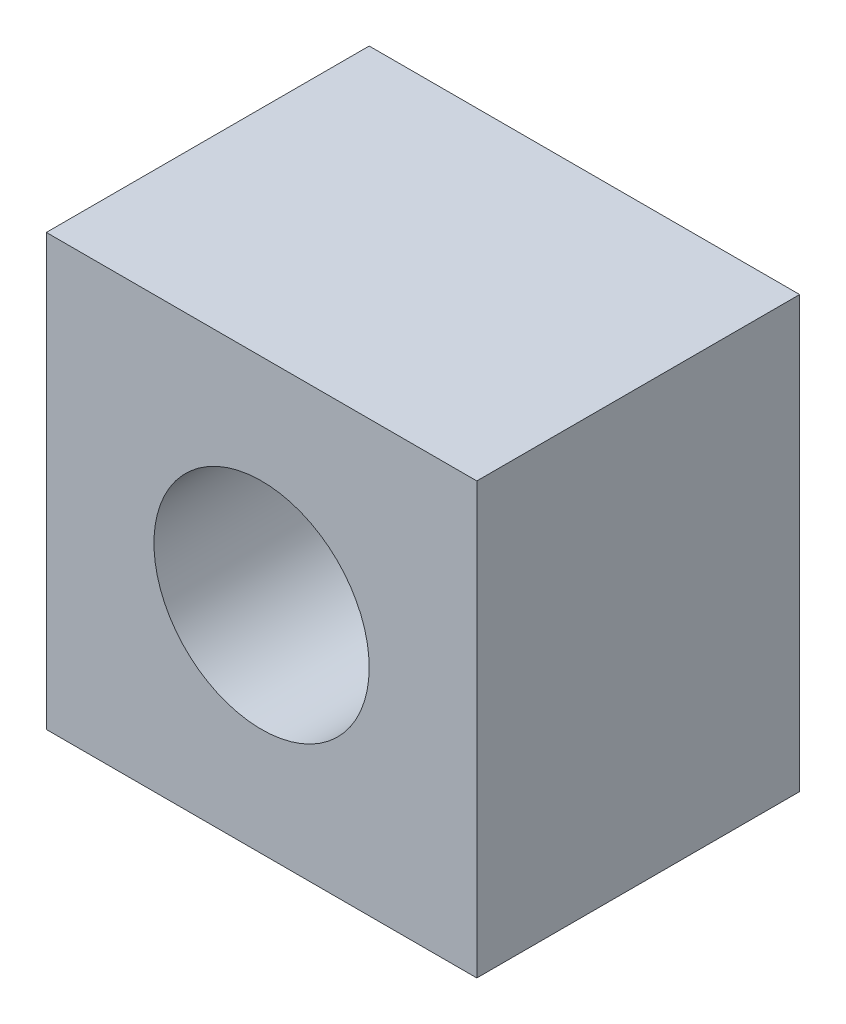
SolidWorks part; units mm, degrees
ref_plane "Plan de face" through (0, 0, 0) normal (0, 0, 1) x (1, 0, 0)
ref_plane "Plan de dessus" through (0, 0, 0) normal (0, 1, 0) x (1, 0, 0)
ref_plane "Plan de droite" through (0, 0, 0) normal (1, 0, 0) x (0, 0, -1)
sketch "Esquisse1" plane through (0, 0, 0) normal (0, 0, 1) x (1, 0, 0)
  line L1 (-6, 6) -> (6, 6)
  line L2 (-6, 6) -> (-6, -6)
  line L3 (-6, -6) -> (6, -6)
  line L4 (6, 6) -> (6, -6)
  line L5 (-6, 6) -> (6, -6) construction
  line L6 (-6, -6) -> (6, 6) construction
  circle A0 centre (0, 0) radius 3
  dimension "D1" = 6
  dimension "D2" = 12
extrude "Boss.-Extru.1" add sketch "Esquisse1" along normal blind 6
sketch "Esquisse2" plane through (0, 0, 0) normal (0, 0, -1) x (-1, 0, 0)
  line L4 (-6, 6) -> (-6, -6)
  line L5 (-6, -6) -> (6, -6)
  line L6 (6, -6) -> (6, 6)
  line L7 (6, 6) -> (-6, 6)
  line L8 (-6, 6) -> (-6, -6)
  line L9 (-6, -6) -> (6, -6)
  line L10 (6, -6) -> (6, 6)
  line L11 (6, 6) -> (-6, 6)
  dimension "D1" = 0
extrude "Boss.-Extru.2" add sketch "Esquisse2" along normal blind 3
hole_wizard "Chambrage pour vis à tête ronde bombée M31" positions "Esquisse3" profile "Esquisse5" counterbore size "M3" standard "Ansi Metric"
sketch "Esquisse3" plane through (0, 0, -3) normal (0, 0, -1) x (-1, 0, 0)
  point P2 (0, 0)
sketch "Esquisse5" plane through (0, 0, -3) normal (1, 0, 0) x (0, 1, 0)
  line L0 (0, 0) -> (0, 6.35)
  line L1 (0, 6.35) -> (1.7, 6.35)
  line L2 (1.7, 6.35) -> (1.7, 2.4)
  line L3 (1.7, 2.4) -> (3.5, 2.4)
  line L4 (3.5, 2.4) -> (3.5, 0)
  line L5 (3.5, 0) -> (0, 0)
  line L10 (0, 6.35) -> (-1.7, 6.35) construction
  line L11 (0, -6.35) -> (0, 107.95) construction
  dimension "Diamètre du perçage" = 3.4
  dimension "Profondeur du perçage" = 6.35
  dimension "Diamètre du chambrage" = 7
  dimension "Profondeur du chambrage" = 2.4
  dimension "Angle de pointe" = 180
